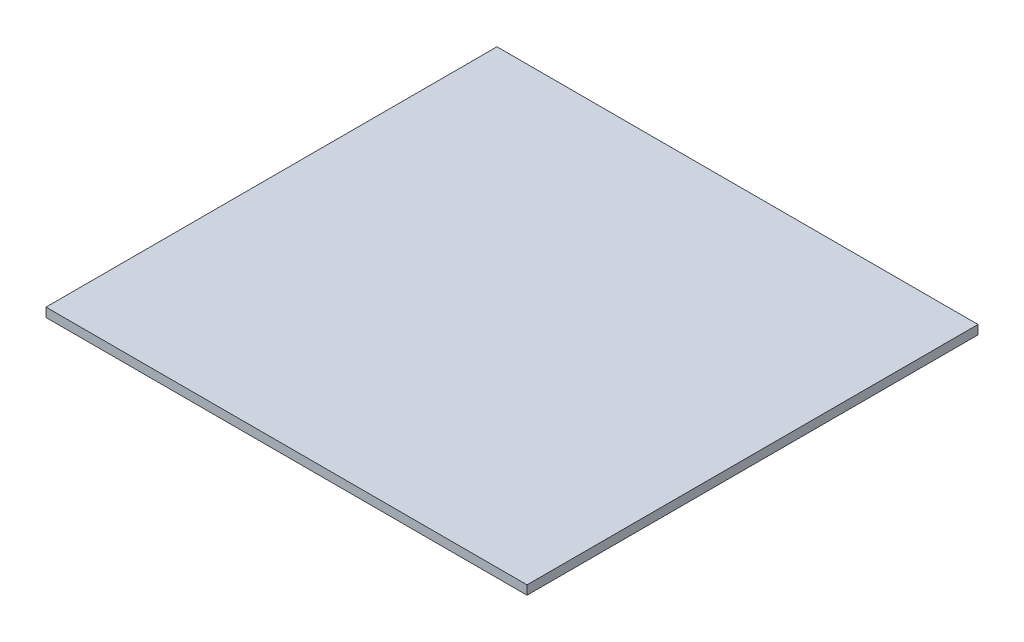
SolidWorks part; units mm, degrees
ref_plane "Спереди" through (0, 0, 0) normal (0, 0, 1) x (1, 0, 0)
ref_plane "Сверху" through (0, 0, 0) normal (0, 1, 0) x (1, 0, 0)
ref_plane "Справа" through (0, 0, 0) normal (1, 0, 0) x (0, 0, -1)
sketch "Эскиз1" plane through (0, 0, 0) normal (0, 1, 0) x (1, 0, 0)
  line L1 (0, 94.0069) -> (160, 94.0069)
  line L2 (0, 94.0069) -> (0, -55.9931)
  line L3 (0, -55.9931) -> (160, -55.9931)
  line L4 (160, 94.0069) -> (160, -55.9931)
extrude "Вытянуть1" add sketch "Эскиз1" along normal blind 3
